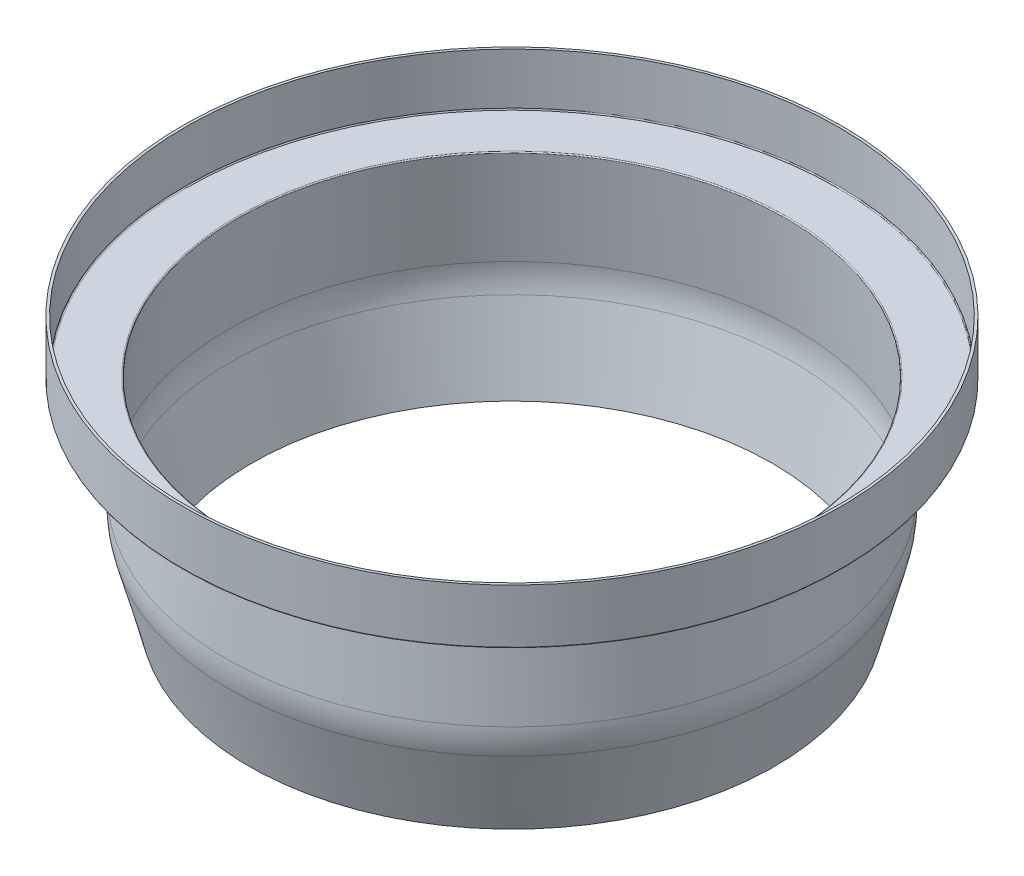
SolidWorks part; units mm, degrees
ref_plane "Ön Düzlem" through (0, 0, 0) normal (0, 0, 1) x (1, 0, 0)
ref_plane "Üst Düzlem" through (0, 0, 0) normal (0, 1, 0) x (1, 0, 0)
ref_plane "Sağ Düzlem" through (0, 0, 0) normal (1, 0, 0) x (0, 0, -1)
sketch "Çizim1" plane through (0, 0, 0) normal (0, 0, 1) x (1, 0, 0)
  line L0 (0, 0) -> (0, 22.4118) construction
  line L1 (-62.6249, 17.4324) -> (-62.6249, 7.6324)
  line L2 (-62.4249, 7.4324) -> (-52.8431, 7.4324)
  line L3 (-52.6439, 7.2149) -> (-54.3191, -11.9328)
  line L4 (-53.8651, -17.1224) -> (-49.8909, -31.9543)
  line L5 (-63.1249, 17.4324) -> (-63.1249, 7.1324)
  line L6 (-62.9249, 6.9324) -> (-53.3888, 6.9324)
  line L7 (-53.1896, 6.7149) -> (-54.8249, -11.9771)
  line L8 (-54.3709, -17.1667) -> (-50.3739, -32.0837)
  line L9 (-62.1249, 17.4324) -> (-62.1249, 8.1324)
  line L10 (-61.9249, 7.9324) -> (-52.2975, 7.9324)
  line L11 (-52.0983, 7.7149) -> (-53.8133, -11.8886)
  line L12 (-53.3593, -17.0782) -> (-49.4079, -31.8249)
  line L13 (-63.1249, 17.4324) -> (-62.6249, 17.4324)
  line L14 (-62.1249, 17.4324) -> (-62.6249, 17.4324)
  line L15 (-50.3739, -32.0837) -> (-49.8909, -31.9543)
  line L16 (-63.1249, 6.9324) -> (-53.1705, 6.9324) construction
  line L17 (-53.1705, 6.9324) -> (-55.0554, -14.6119) construction
  line L18 (-62.6249, 7.4324) -> (-52.6249, 7.4324) construction
  line L19 (-52.6249, 7.4324) -> (-54.5496, -14.5676) construction
  line L20 (-62.1249, 7.9324) -> (-52.0792, 7.9324) construction
  line L21 (-52.0792, 7.9324) -> (-54.0439, -14.5234) construction
  line L22 (-62.1249, 17.4324) -> (-62.1249, 7.9324) construction
  line L23 (-62.6249, 17.4324) -> (-62.6249, 7.4324) construction
  line L24 (-63.1249, 17.4324) -> (-63.1249, 6.9324) construction
  line L25 (-54.0439, -14.5234) -> (-49.4079, -31.8249) construction
  line L26 (-55.0554, -14.6119) -> (-50.3739, -32.0837) construction
  line L27 (-54.5496, -14.5676) -> (-49.8909, -31.9543) construction
  arc A0 (-53.3888, 6.9324) -> (-53.1896, 6.7149) centre (-53.3888, 6.7324) cw
  arc A1 (-52.8431, 7.4324) -> (-52.6439, 7.2149) centre (-52.8431, 7.2324) cw
  arc A2 (-52.2975, 7.9324) -> (-52.0983, 7.7149) centre (-52.2975, 7.7324) cw
  arc A3 (-62.1249, 8.1324) -> (-61.9249, 7.9324) centre (-61.9249, 8.1324) ccw
  arc A4 (-62.4249, 7.4324) -> (-62.6249, 7.6324) centre (-62.4249, 7.6324) cw
  arc A5 (-63.1249, 7.1324) -> (-62.9249, 6.9324) centre (-62.9249, 7.1324) ccw
  arc A6 (-53.8133, -11.8886) -> (-53.3593, -17.0782) centre (-38.8704, -13.1959) ccw
  arc A7 (-54.8249, -11.9771) -> (-54.3709, -17.1667) centre (-39.882, -13.2844) ccw
  arc A8 (-54.3191, -11.9328) -> (-53.8651, -17.1224) centre (-39.3762, -13.2401) ccw
  point P24 (-52.6249, 7.4324)
  dimension "D9" = 0.2
  dimension "D1" = 15
  dimension "D3" = 85
  dimension "D4" = 160
  dimension "D7" = 0.5
  dimension "D8" = 0.5
revolve "Döndür1" add sketch "Çizim1" angle 360 about L0
